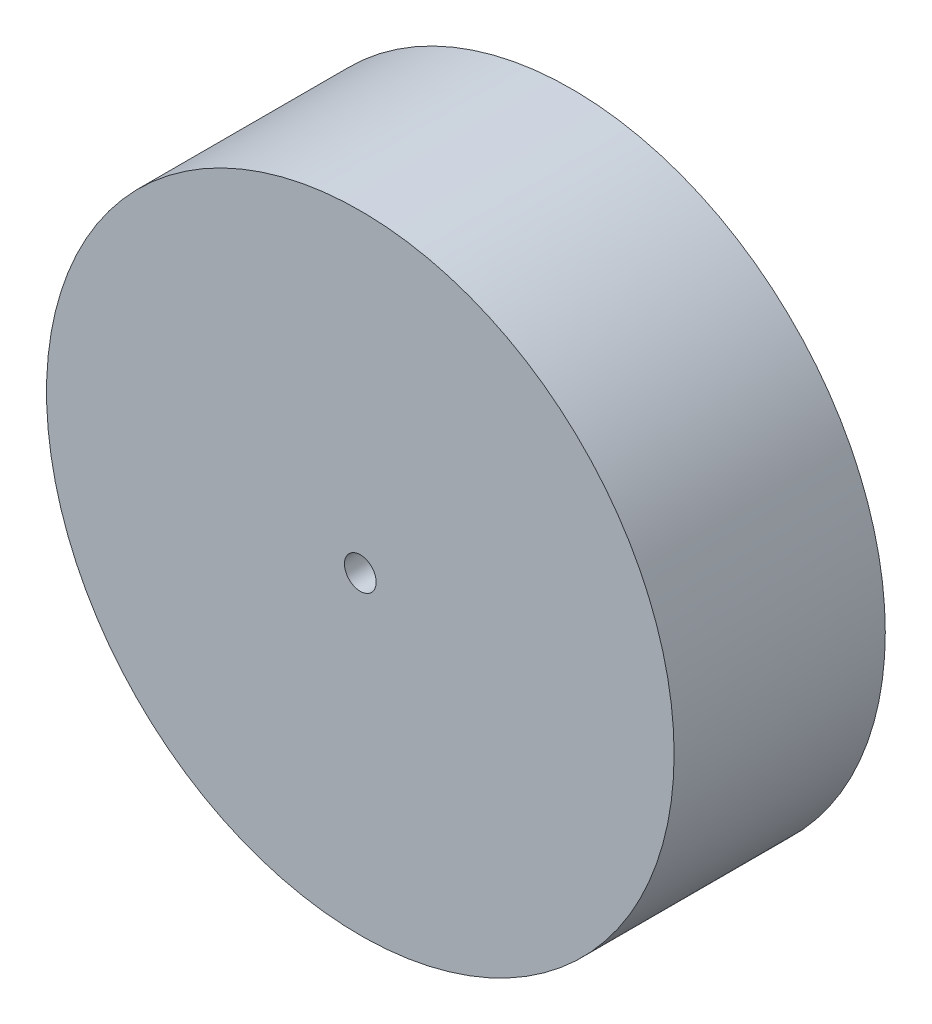
SolidWorks part; units mm, degrees
material "Rubber"
ref_plane "Front Plane" through (0, 0, 0) normal (0, 0, 1) x (1, 0, 0)
ref_plane "Top Plane" through (0, 0, 0) normal (0, 1, 0) x (1, 0, 0)
ref_plane "Right Plane" through (0, 0, 0) normal (1, 0, 0) x (0, 0, -1)
sketch "Sketch1" plane through (0, 0, 0) normal (0, 0, 1) x (1, 0, 0)
  circle A0 centre (0, 0) radius 0.75
  circle A1 centre (0, 0) radius 14.859
  dimension "D1" = 29.718
  dimension "D2" = 1.5
extrude "Boss-Extrude1" add sketch "Sketch1" along normal blind 10
